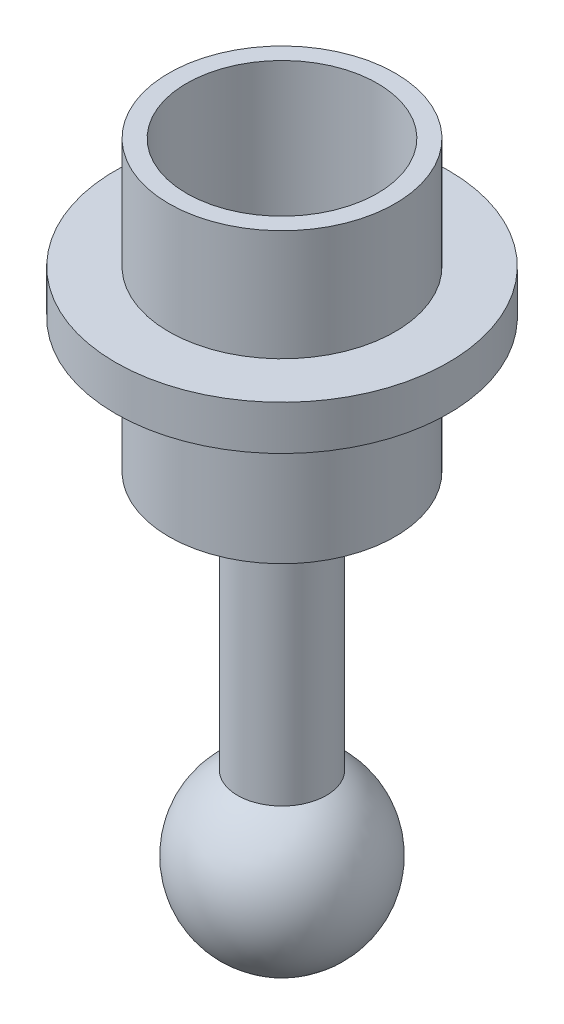
SolidWorks part; units mm, degrees
ref_plane "Front Plane" through (0, 0, 0) normal (0, 0, 1) x (1, 0, 0)
ref_plane "Top Plane" through (0, 0, 0) normal (0, 1, 0) x (1, 0, 0)
ref_plane "Right Plane" through (0, 0, 0) normal (1, 0, 0) x (0, 0, -1)
sketch "Sketch2" plane through (0, 0, 0) normal (0, 1, 0) x (1, 0, 0)
  circle A0 centre (0, 0) radius 5.1
  dimension "D1" = 10.2
extrude "Boss-Extrude1" add sketch "Sketch2" along normal blind 1
sketch "Sketch3" plane through (0, 1, 0) normal (0, 1, 0) x (1, 0, 0)
  circle A0 centre (0, 0) radius 5.1
  circle A1 centre (0, 0) radius 4.3
  dimension "D1" = 10.2
  dimension "D2" = 8.6
extrude "Boss-Extrude2" add sketch "Sketch3" along normal blind 12
sketch "Sketch6" plane through (0, 1, 0) normal (0, 1, 0) x (1, 0, 0)
  line L0 (0, 0) -> (0, 3.3)
  line L1 (0, 0) -> (-0.8541, 3.1876) construction
  line L2 (0, 0) -> (0.8541, 3.1876) construction
  line L3 (0.8541, 3.1876) -> (0.647, 2.4148)
  line L4 (-0.8541, 3.1876) -> (-0.647, 2.4148)
  line L5 (3.1876, 0.8541) -> (2.4148, 0.647)
  line L6 (2.3335, 2.3335) -> (1.7678, 1.7678)
  line L7 (2.3335, -2.3335) -> (1.7678, -1.7678)
  line L8 (3.1876, -0.8541) -> (2.4148, -0.647)
  line L9 (-0.8541, -3.1876) -> (-0.647, -2.4148)
  line L10 (0.8541, -3.1876) -> (0.647, -2.4148)
  line L11 (-3.1876, -0.8541) -> (-2.4148, -0.647)
  line L12 (-2.3335, -2.3335) -> (-1.7678, -1.7678)
  line L13 (-2.3335, 2.3335) -> (-1.7678, 1.7678)
  line L14 (-3.1876, 0.8541) -> (-2.4148, 0.647)
  arc A0 (0.8541, 3.1876) -> (-0.8541, 3.1876) centre (0, 0) ccw
  arc A1 (0.647, 2.4148) -> (-0.647, 2.4148) centre (0, 0) ccw
  arc A2 (3.1876, 0.8541) -> (2.3335, 2.3335) centre (0, 0) ccw
  arc A3 (2.4148, 0.647) -> (1.7678, 1.7678) centre (0, 0) ccw
  arc A4 (2.3335, -2.3335) -> (3.1876, -0.8541) centre (0, 0) ccw
  arc A5 (1.7678, -1.7678) -> (2.4148, -0.647) centre (0, 0) ccw
  arc A6 (-0.8541, -3.1876) -> (0.8541, -3.1876) centre (0, 0) ccw
  arc A7 (-0.647, -2.4148) -> (0.647, -2.4148) centre (0, 0) ccw
  arc A8 (-3.1876, -0.8541) -> (-2.3335, -2.3335) centre (0, 0) ccw
  arc A9 (-2.4148, -0.647) -> (-1.7678, -1.7678) centre (0, 0) ccw
  arc A10 (-2.3335, 2.3335) -> (-3.1876, 0.8541) centre (0, 0) ccw
  arc A11 (-1.7678, 1.7678) -> (-2.4148, 0.647) centre (0, 0) ccw
  point P29 (0, 0)
  dimension "D1" = 6.6
  dimension "D2" = 5
  dimension "D3" = 15
  dimension "D4" = 15
  dimension "D5" = 6
extrude "Cut-Extrude2" cut sketch "Sketch6" against normal blind 1 contours A11 L13 A10 L14 | A3 L5 A2 L6 | A5 L7 A4 L8 | A7 L9 A6 L10 | A9 L11 A8 L12 | A1 L4 A0 L3
ref_plane "Plane2" through (0, 6, 0) normal (0, 1, 0) x (1, 0, 0)
sketch "Sketch7" plane through (0, 6, 0) normal (0, 1, 0) x (1, 0, 0)
  circle A0 centre (0, 0) radius 7.5
  circle A1 centre (0, 0) radius 5.1
  dimension "D1" = 15
  dimension "D2" = 10.2
extrude "Boss-Extrude4" add sketch "Sketch7" along normal blind 2
sketch "Sketch8" plane through (0, 0, 0) normal (1, 0, 0) x (0, 0, -1)
  line L0 (0, 0) -> (0, -15)
  line L1 (2, -11.6519) -> (2, 0)
  line L2 (-2, 0) -> (-2, -11.6519)
  line L3 (-5.1, 0) -> (5.1, 0) construction
  line L5 (0.8541, 0) -> (2.3335, 0) construction
  line L6 (2, 0) -> (-2, 0)
  line L7 (0, -15) -> (0, -18.9)
  circle A0 centre (0, -15) radius 3.9
  dimension "D2" = 7.8
  dimension "D1" = 15
  dimension "D3" = 4
revolve "Revolve1" add sketch "Sketch8" angle 360 about L0
